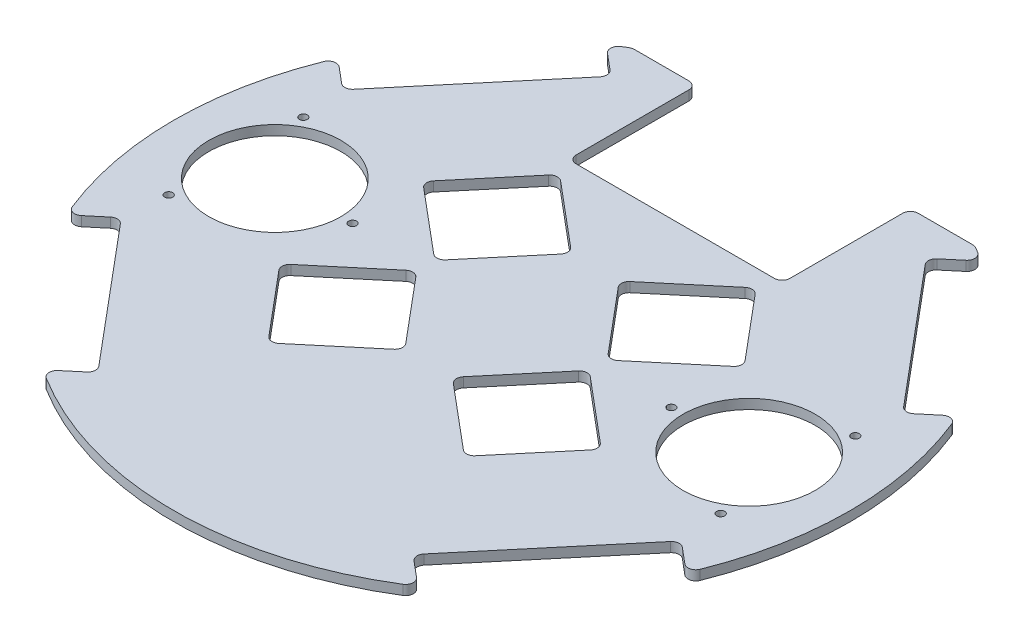
SolidWorks part; units mm, degrees
ref_plane "Plano frontal" through (0, 0, 0) normal (0, 0, 1) x (1, 0, 0)
ref_plane "Plano superior" through (0, 0, 0) normal (0, 1, 0) x (1, 0, 0)
ref_plane "Plano direito" through (0, 0, 0) normal (1, 0, 0) x (0, 0, -1)
sketch "Esboço1" plane through (0, 0, 0) normal (0, 1, 0) x (1, 0, 0)
  circle A0 centre (0, 0) radius 87
  dimension "D1" = 174
extrude "Ressalto-extrusão1" add sketch "Esboço1" along normal blind 2.5
sketch "Esboço2" plane through (0, 2.5, 0) normal (0, 1, 0) x (1, 0, 0)
  line L0 (87, 0) -> (-87, 0) construction
  line L1 (0, 87) -> (0, -87) construction
  line L2 (0, 0) -> (66.6459, -55.9225) construction
  line L3 (0, 0) -> (66.6459, 55.9225) construction
  line L4 (48.2004, 72.4274) -> (79.697, 34.8912) construction
  line L5 (66.6459, 55.9225) -> (82.3942, 37.1544)
  line L6 (82.3942, 37.1544) -> (79.697, 34.8912)
  line L7 (79.697, 34.8912) -> (72.0365, 28.4633)
  line L8 (72.0365, 28.4633) -> (40.5399, 65.9995)
  line L9 (40.5399, 65.9995) -> (48.2004, 72.4274)
  line L10 (48.2004, 72.4274) -> (50.8976, 74.6906)
  line L11 (50.8976, 74.6906) -> (66.6459, 55.9225)
  line L12 (50.8976, -74.6906) -> (82.3942, -37.1544)
  line L13 (48.2004, -72.4274) -> (79.697, -34.8912) construction
  line L14 (50.8976, -74.6906) -> (48.2004, -72.4274)
  line L15 (48.2004, -72.4274) -> (40.5399, -65.9995)
  line L16 (40.5399, -65.9995) -> (72.0365, -28.4633)
  line L17 (72.0365, -28.4633) -> (79.697, -34.8912)
  line L18 (79.697, -34.8912) -> (82.3942, -37.1544)
  line L19 (-48.2004, 72.4274) -> (-79.697, 34.8912) construction
  line L20 (-72.0365, 28.4633) -> (-40.5399, 65.9995)
  line L21 (-48.2004, 72.4274) -> (-50.8976, 74.6906)
  line L22 (-40.5399, 65.9995) -> (-48.2004, 72.4274)
  line L23 (-50.8976, 74.6906) -> (-66.6459, 55.9225)
  line L24 (-79.697, 34.8912) -> (-72.0365, 28.4633)
  line L25 (-82.3942, 37.1544) -> (-79.697, 34.8912)
  line L26 (-66.6459, 55.9225) -> (-82.3942, 37.1544)
  line L27 (-48.2004, -72.4274) -> (-79.697, -34.8912) construction
  line L28 (-79.697, -34.8912) -> (-82.3942, -37.1544)
  line L29 (-72.0365, -28.4633) -> (-79.697, -34.8912)
  line L30 (-40.5399, -65.9995) -> (-72.0365, -28.4633)
  line L31 (-48.2004, -72.4274) -> (-40.5399, -65.9995)
  line L32 (-50.8976, -74.6906) -> (-48.2004, -72.4274)
  line L33 (-50.8976, -74.6906) -> (-82.3942, -37.1544)
  circle A0 centre (0, 0) radius 87 construction
  point P14 (66.6459, 55.9225)
  point P21 (66.6459, -55.9225)
  point P32 (-66.6459, 55.9225)
  point P39 (-66.6459, -55.9225)
  dimension "D1" = 40
  dimension "D2" = 40
  dimension "D3" = 49
  dimension "D4" = 10
  dimension "D5" = 49
  dimension "D6" = 49
  dimension "D7" = 10
extrude "Corte-extrusão1" cut sketch "Esboço2" against normal blind 2.5
sketch "Esboço3" plane through (0, 2.5, 0) normal (0, 1, 0) x (1, 0, 0)
  line L0 (0, 0) -> (0, 87) construction
  line L1 (-44.0908, 87) -> (44.0908, 87)
  line L2 (44.0908, 87) -> (44.0908, 75)
  line L3 (44.0908, 75) -> (0, 75)
  line L4 (0, 75) -> (-44.0908, 75)
  line L5 (-44.0908, 75) -> (-44.0908, 87)
  line L6 (-27.5, 75) -> (-27.5, 42)
  line L7 (-27.5, 42) -> (27.5, 42)
  line L8 (27.5, 42) -> (27.5, 75)
  arc A0 (48.2004, 72.4274) -> (-48.2004, 72.4274) centre (0, 0) ccw construction
  point P9 (0, 87)
  point P15 (0, 42)
  arc M12 (48.2004, 72.4274) -> (-48.2004, 72.4274) centre (0, 0) ccw
  dimension "D1" = 75
  dimension "D2" = 55
  dimension "D3" = 33
extrude "Corte-extrusão2" cut sketch "Esboço3" against normal blind 2.5 contours L7 L0 L4 L6 | L0 L7 L8 L3 | L0 L3 M12 | L4 L0 M12
fillet "Filete2" radius 2 22 edges at (-48.2004, 1.25, 72.4274) (-40.5399, 1.25, 65.9995) (-72.0365, 1.25, 28.4633) (-79.697, 1.25, 34.8912) (-79.697, 1.25, -34.8912) (-72.0365, 1.25, -28.4633) (-40.5399, 1.25, -65.9995) (-48.2004, 1.25, -72.4274) (-44.0908, 1.25, -75) (-27.5, 1.25, -75) (-27.5, 1.25, -42) (27.5, 1.25, -42) (27.5, 1.25, -75) (44.0908, 1.25, -75) (48.2004, 1.25, -72.4274) (40.5399, 1.25, -65.9995) (72.0365, 1.25, -28.4633) (79.697, 1.25, -34.8912) (79.697, 1.25, 34.8912) (72.0365, 1.25, 28.4633) (48.2004, 1.25, 72.4274) (40.5399, 1.25, 65.9995)
sketch "Esboço4" plane through (0, 2.5, 0) normal (0, 1, 0) x (1, 0, 0)
  line L0 (-87, 0) -> (87, 0) construction
  line L1 (0, 0) -> (0, 42) construction
  line L2 (-25.5, 42) -> (25.5, 42) construction
  arc A0 (80.7589, -32.3575) -> (80.7589, 32.3575) centre (0, 0) ccw construction
  circle A1 centre (61, 0) radius 17
  circle A3 centre (-61, 0) radius 17
  point P6 (61, 0)
  point P15 (41, 0)
  point P16 (-41, 0)
  point P17 (-61, 0)
  dimension "D2" = 34
  dimension "D1" = 26
  dimension "D3" = 20
extrude "Corte-extrusão3" cut sketch "Esboço4" against normal blind 4
sketch "Esboço7" plane through (0, 2.5, 0) normal (0, 1, 0) x (1, 0, 0)
  line L0 (0, 0) -> (-56.2882, -47.2314) construction
  line L1 (-41.8255, -64.4674) -> (-70.7509, -29.9954) construction
  line L2 (-40.0561, -19.9043) -> (-26.5576, -35.9913)
  line L3 (-23.7399, -36.2378) -> (-7.653, -22.7392)
  line L4 (-7.4065, -19.9216) -> (-20.905, -3.8346)
  line L5 (-23.7227, -3.5881) -> (-39.8096, -17.0867)
  line L6 (0, -87) -> (0, 42) construction
  line L7 (-25.5, 42) -> (25.5, 42) construction
  line L8 (-87, 0) -> (87, 0) construction
  line L9 (-23.7227, 3.5881) -> (-39.8096, 17.0867)
  line L10 (-7.4065, 19.9216) -> (-20.905, 3.8346)
  line L11 (-23.7399, 36.2378) -> (-7.653, 22.7392)
  line L12 (-40.0561, 19.9043) -> (-26.5576, 35.9913)
  line L13 (40.0561, 19.9043) -> (26.5576, 35.9913)
  line L14 (23.7399, 36.2378) -> (7.653, 22.7392)
  line L15 (7.4065, 19.9216) -> (20.905, 3.8346)
  line L16 (23.7227, 3.5881) -> (39.8096, 17.0867)
  line L17 (23.7227, -3.5881) -> (39.8096, -17.0867)
  line L18 (7.4065, -19.9216) -> (20.905, -3.8346)
  line L19 (23.7399, -36.2378) -> (7.653, -22.7392)
  line L20 (40.0561, -19.9043) -> (26.5576, -35.9913)
  arc A0 (-20.905, -3.8346) -> (-23.7227, -3.5881) centre (-22.4371, -5.1202) ccw
  arc A1 (-7.653, -22.7392) -> (-7.4065, -19.9216) centre (-8.9386, -21.2071) ccw
  arc A2 (-40.0561, -19.9043) -> (-39.8096, -17.0867) centre (-38.5241, -18.6187) cw
  arc A3 (-26.5576, -35.9913) -> (-23.7399, -36.2378) centre (-25.0255, -34.7057) ccw
  arc A4 (-45.8895, -73.9131) -> (45.8895, -73.9131) centre (0, 0) ccw construction
  arc A5 (-80.7589, 32.3575) -> (-80.7589, -32.3575) centre (0, 0) ccw construction
  arc A6 (80.7589, -32.3575) -> (80.7589, 32.3575) centre (0, 0) ccw construction
  arc A7 (-26.5576, 35.9913) -> (-23.7399, 36.2378) centre (-25.0255, 34.7057) cw
  arc A8 (-40.0561, 19.9043) -> (-39.8096, 17.0867) centre (-38.5241, 18.6187) ccw
  arc A9 (-7.653, 22.7392) -> (-7.4065, 19.9216) centre (-8.9386, 21.2071) cw
  arc A10 (-20.905, 3.8346) -> (-23.7227, 3.5881) centre (-22.4371, 5.1202) cw
  arc A11 (20.905, 3.8346) -> (23.7227, 3.5881) centre (22.4371, 5.1202) ccw
  arc A12 (7.653, 22.7392) -> (7.4065, 19.9216) centre (8.9386, 21.2071) ccw
  arc A13 (40.0561, 19.9043) -> (39.8096, 17.0867) centre (38.5241, 18.6187) cw
  arc A14 (26.5576, 35.9913) -> (23.7399, 36.2378) centre (25.0255, 34.7057) ccw
  arc A15 (26.5576, -35.9913) -> (23.7399, -36.2378) centre (25.0255, -34.7057) cw
  arc A16 (40.0561, -19.9043) -> (39.8096, -17.0867) centre (38.5241, -18.6187) ccw
  arc A17 (7.653, -22.7392) -> (7.4065, -19.9216) centre (8.9386, -21.2071) cw
  arc A18 (20.905, -3.8346) -> (23.7227, -3.5881) centre (22.4371, -5.1202) cw
  point P8 (-33.3069, -27.9478)
  point P14 (-6.1209, -21.4537)
  point P17 (-41.3417, -18.3722)
  point P20 (-25.272, -37.5233)
  point P48 (-25.272, 37.5233)
  point P49 (-41.3417, 18.3722)
  point P50 (-6.1209, 21.4537)
  point P51 (-33.3069, 27.9478)
  point P76 (33.3069, 27.9478)
  point P77 (6.1209, 21.4537)
  point P78 (41.3417, 18.3722)
  point P79 (25.272, 37.5233)
  point P80 (25.272, -37.5233)
  point P81 (41.3417, -18.3722)
  point P82 (6.1209, -21.4537)
  point P83 (33.3069, -27.9478)
  dimension "D4" = 2
  dimension "D1" = 25
  dimension "D2" = 25
  dimension "D3" = 30
extrude "Corte-extrusão5" cut sketch "Esboço7" against normal blind 3
sketch "Esboço8" plane through (0, 2.5, 0) normal (0, 1, 0) x (1, 0, 0)
  line L0 (41, 0) -> (61, 0) construction
  line L1 (61, 0) -> (71, -17.3205) construction
  line L2 (61, 0) -> (71, 17.3205) construction
  line L3 (0, 0) -> (0, 35.1541) construction
  line L4 (-61, 0) -> (-71, 17.3205) construction
  line L5 (-61, 0) -> (-71, -17.3205) construction
  line L6 (-41, 0) -> (-61, 0) construction
  circle A0 centre (61, 0) radius 20 construction
  circle A1 centre (61, 0) radius 17 construction
  circle A2 centre (-61, 0) radius 20 construction
  point P5 (41, 0)
  point P16 (-41, 0)
  dimension "D1" = 40
  dimension "D2" = 120
  dimension "D3" = 120
hole_wizard "Furo roscado de M2.51" positions "3DSketch1" profile "Esboço9" tap size "M2.5" standard "ISO" end condition up to next
sketch3d "3DSketch1"
  point P0 (-71, 2.5, -17.3205)
  point P3 (-41, 2.5, 0)
  point P6 (-71, 2.5, 17.3205)
  point P9 (41, 2.5, 0)
  point P12 (71, 2.5, -17.3205)
  point P15 (71, 2.5, 17.3205)
sketch "Esboço9" plane through (-71, 2.5, -17.3205) normal (1, 0, 0) x (0, 0, 1)
  line L0 (0, 0) -> (0, 2.5)
  line L1 (0, 2.5) -> (1.025, 2.5)
  line L2 (1.025, 2.5) -> (1.025, 0)
  line L5 (1.025, 0) -> (0, 0)
  line L11 (0, -6.35) -> (0, 107.95) construction
  dimension "Thru Tap Drill Dia." = 2.05
  dimension "Thru Tap Drill Depth" = 2.5
cosmetic thread "Rosca de furo1" parameters "D2"=2.5
cosmetic thread "Rosca de furo2" parameters "D2"=2.5
cosmetic thread "Rosca de furo3" parameters "D2"=2.5
cosmetic thread "Rosca de furo4" parameters "D2"=2.5
cosmetic thread "Rosca de furo5" parameters "D2"=2.5
cosmetic thread "Rosca de furo6" parameters "D2"=2.5
